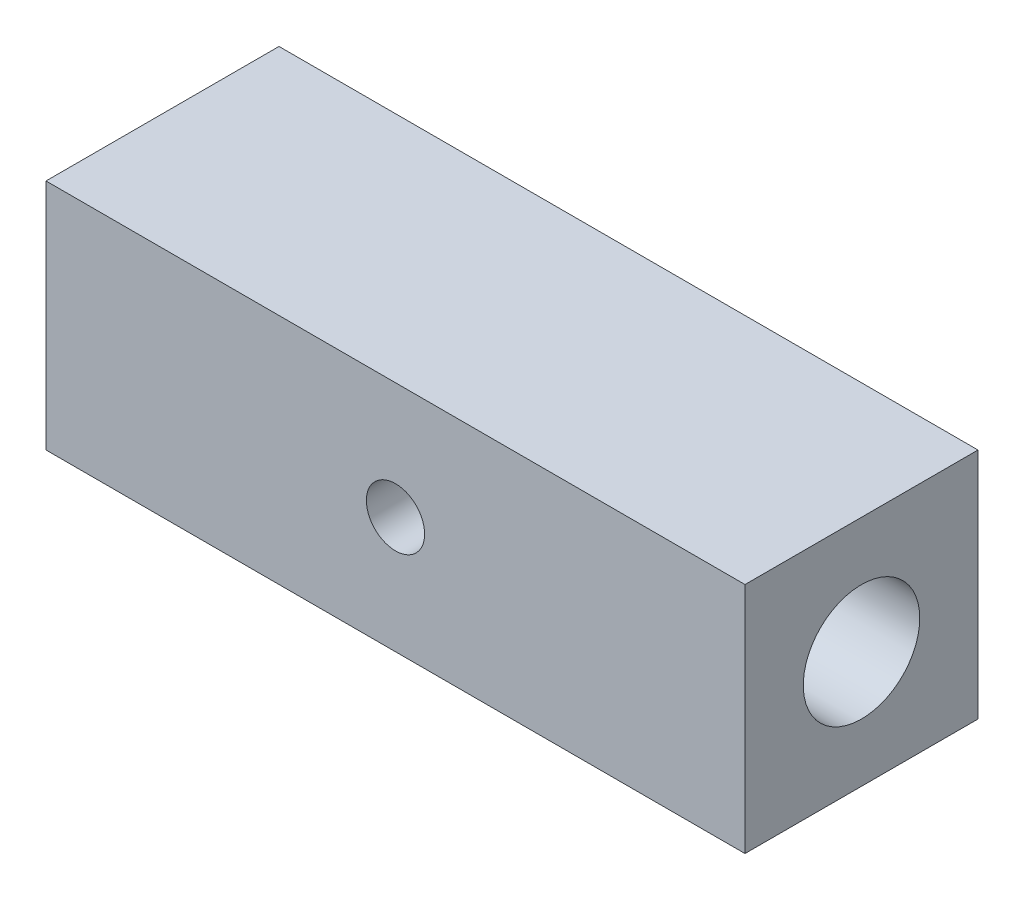
SolidWorks part; units mm, degrees
ref_plane "Front Plane" through (0, 0, 0) normal (0, 0, 1) x (1, 0, 0)
ref_plane "Top Plane" through (0, 0, 0) normal (0, 1, 0) x (1, 0, 0)
ref_plane "Right Plane" through (0, 0, 0) normal (1, 0, 0) x (0, 0, -1)
sketch "Sketch1" plane through (0, 0, 0) normal (0, 0, 1) x (1, 0, 0)
  line L1 (-76.2, 25.4) -> (0, 25.4)
  line L2 (-76.2, 25.4) -> (-76.2, 0)
  line L3 (-76.2, 0) -> (0, 0)
  line L4 (0, 25.4) -> (0, 0)
  circle A0 centre (-38.1, 12.7) radius 3.175
  dimension "D3" = 6.35
  dimension "D1" = 25.4
  dimension "D2" = 76.2
extrude "Boss-Extrude1" add sketch "Sketch1" along normal blind 25.4
sketch "Sketch2" plane through (0, 0, 0) normal (1, 0, 0) x (0, 0, -1)
  circle A0 centre (-12.7, 12.7) radius 6.35
  dimension "D1" = 12.7
extrude "Cut-Extrude1" cut sketch "Sketch2" against normal through all
